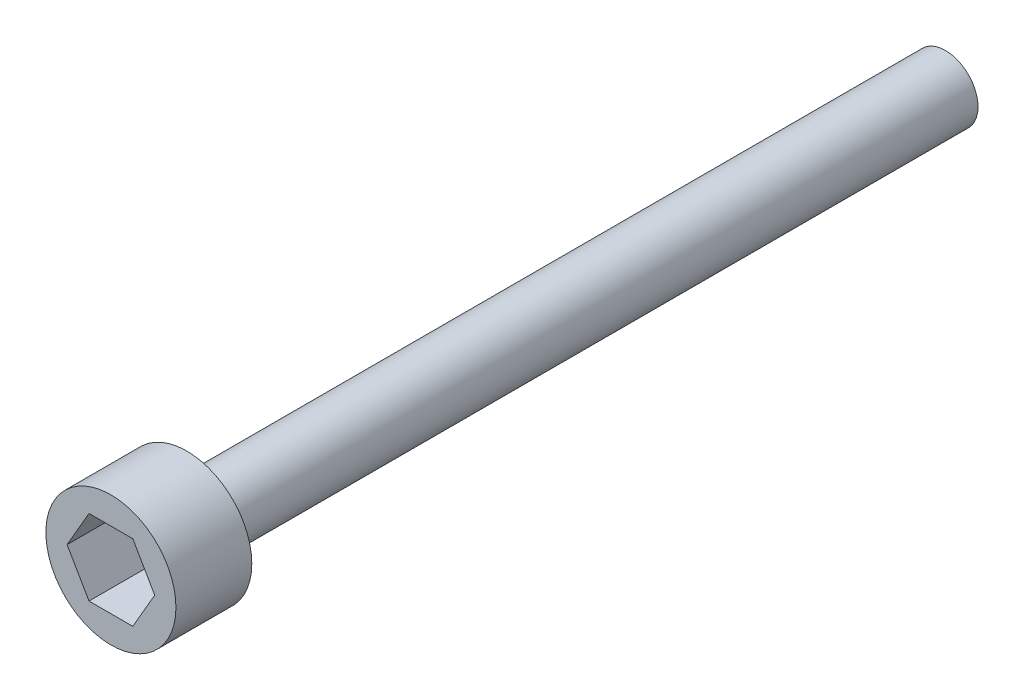
SolidWorks part; units mm, degrees
ref_plane "Front Plane" through (0, 0, 0) normal (0, 0, 1) x (1, 0, 0)
ref_plane "Top Plane" through (0, 0, 0) normal (0, 1, 0) x (1, 0, 0)
ref_plane "Right Plane" through (0, 0, 0) normal (1, 0, 0) x (0, 0, -1)
sketch "Sketch1" plane through (0, 0, 0) normal (0, 0, 1) x (1, 0, 0)
  circle A0 centre (0, 0) radius 3
  dimension "D1" = 6
extrude "Head Boss-Extrude1" add sketch "Sketch1" along normal blind 3.5
sketch "Sketch3" plane through (0, 0, 3.5) normal (0, 0, 1) x (1, 0, 0)
  line L0 (-1.0104, 1.75) -> (1.0104, 1.75)
  line L1 (1.0104, 1.75) -> (2.0207, 0)
  line L2 (2.0207, 0) -> (1.0104, -1.75)
  line L3 (1.0104, -1.75) -> (-1.0104, -1.75)
  line L4 (-1.0104, -1.75) -> (-2.0207, 0)
  line L5 (-2.0207, 0) -> (-1.0104, 1.75)
  line L6 (-2.0207, 0) -> (0, 0) construction
  line L7 (2.0207, 0) -> (0, 0) construction
  line L8 (-1.0104, -1.75) -> (0, 0) construction
  line L9 (0, 0) -> (1.0104, 1.75) construction
  line L10 (-1.0104, 1.75) -> (0, 0) construction
  line L11 (0, 0) -> (1.0104, -1.75) construction
  dimension "D1" = 60
  dimension "D2" = 60
  dimension "D3" = 60
  dimension "D4" = 60
  dimension "D5" = 60
  dimension "D6" = 3.5
extrude "Head Hex Cut-Extrude1" cut sketch "Sketch3" against normal blind 2.8
sketch "Sketch2" plane through (0, 0, 0) normal (0, 0, 1) x (1, 0, 0)
  circle A0 centre (0, 0) radius 1.5
  dimension "D1" = 3
extrude "Screw Boss-Extrude2" add sketch "Sketch2" against normal blind 35
